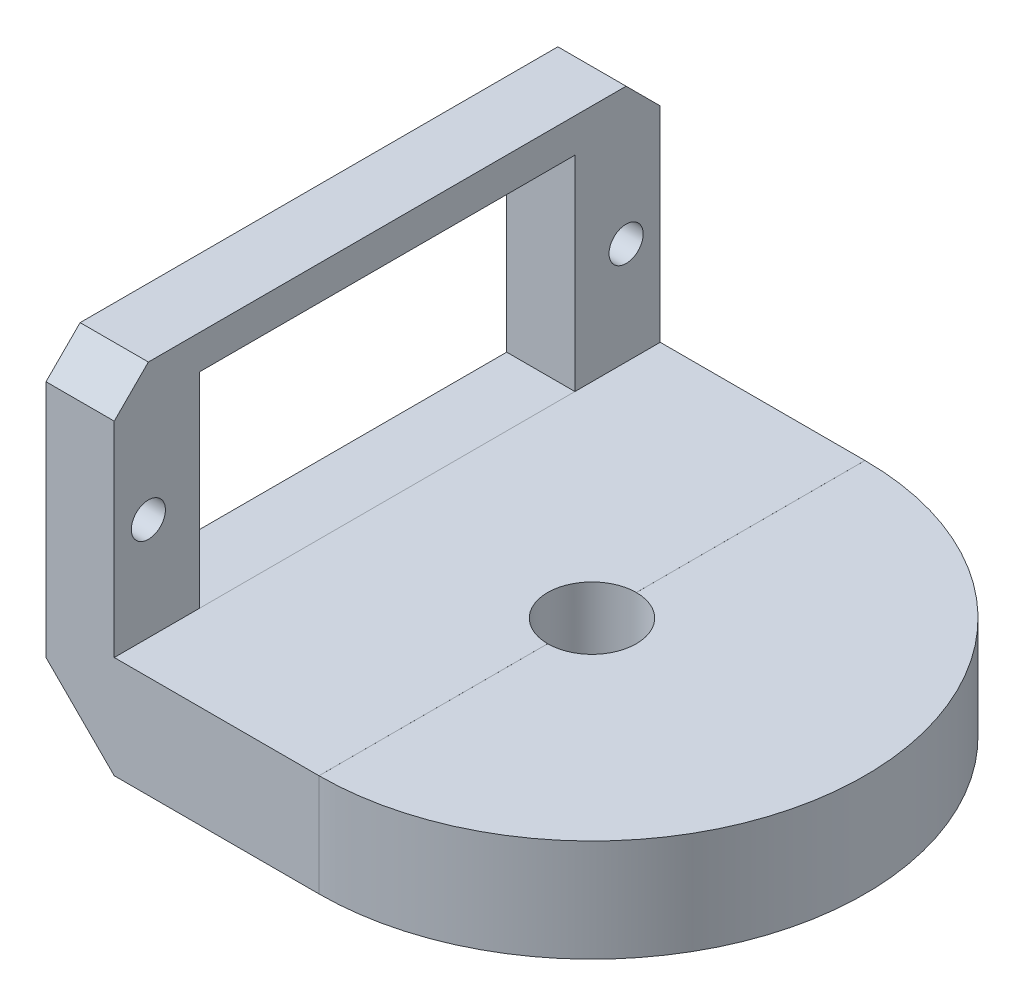
SolidWorks part; units mm, degrees
ref_plane "前视基准面" through (0, 0, 0) normal (0, 0, 1) x (1, 0, 0)
ref_plane "上视基准面" through (0, 0, 0) normal (0, 1, 0) x (1, 0, 0)
ref_plane "右视基准面" through (0, 0, 0) normal (1, 0, 0) x (0, 0, -1)
other "Configuration Table"
sketch "Sketch1" plane through (0, 0, 0) normal (1, 0, 0) x (0, 0, -1)
  line L1 (0, 0) -> (32, 0)
  line L2 (0, 0) -> (0, 16)
  line L3 (0, 16) -> (32, 16)
  line L4 (32, 0) -> (32, 16)
  line L5 (5, 2) -> (27, 2)
  line L6 (5, 2) -> (5, 14)
  line L7 (5, 14) -> (27, 14)
  line L8 (27, 2) -> (27, 14)
  dimension "D1" = 16
  dimension "D2" = 32
  dimension "D3" = 2
  dimension "D4" = 2
  dimension "D5" = 22
  dimension "D6" = 5
extrude "Boss-Extrude1" add sketch "Sketch1" along normal blind 4
sketch "Sketch3" plane through (4, 0, 0) normal (1, 0, 0) x (0, 0, -1)
  line L5 (0, 16) -> (0, 0) construction
  line L6 (32, 0) -> (0, 0)
  line L7 (32, 0) -> (32, 2.0013)
  line L8 (32, 2.0013) -> (0, 2.0013)
  line L9 (0, 0) -> (0, 2.0013)
extrude "Boss-Extrude3" add sketch "Sketch3" along normal blind 12
sketch "Sketch7" plane through (0, 0, 0) normal (0, -1, 0) x (1, 0, 0)
  line L0 (0, -32) -> (0, 0) construction
  line L3 (0, 0) -> (16, 0)
  line L4 (0, 0) -> (0, -32)
  line L5 (0, -32) -> (16, -32)
  arc A0 (16, -32) -> (16, 0) centre (16, -16) ccw
extrude "Boss-Extrude5" add sketch "Sketch7" along normal blind 4 and the other way blind 2
chamfer "Chamfer1" distance 4 angle 45 1 edges at (0, -4, -16)
sketch "Sketch8" plane through (0, -4, 0) normal (0, -1, 0) x (1, 0, 0)
  circle A0 centre (16, -16) radius 2.6
  dimension "D1" = 5.2
extrude "Cut-Extrude2" cut sketch "Sketch8" against normal through all
sketch "Sketch9" plane through (0, 0, 0) normal (-1, 0, 0) x (0, 0, 1)
  line L0 (-27, 8) -> (-32, 8) construction
  line L1 (-27, 2) -> (-27, 14) construction
  line L2 (-32, 0) -> (-32, 16) construction
  line L3 (-32, 8) -> (-30, 8) construction
  line L4 (-5, 8) -> (0, 8) construction
  line L5 (-5, 14) -> (-5, 2) construction
  line L6 (0, 16) -> (0, 0) construction
  line L7 (0, 8) -> (-2, 8) construction
  circle A0 centre (-30, 8) radius 1
  circle A1 centre (-2, 8) radius 1
  dimension "D3" = 2
  dimension "D4" = 2
  dimension "D1" = 2
  dimension "D2" = 2
extrude "Cut-Extrude3" cut sketch "Sketch9" against normal through all
chamfer "Chamfer2" distance 2 angle 45 2 edges at (2, 16, 0) (2, 16, -32)
